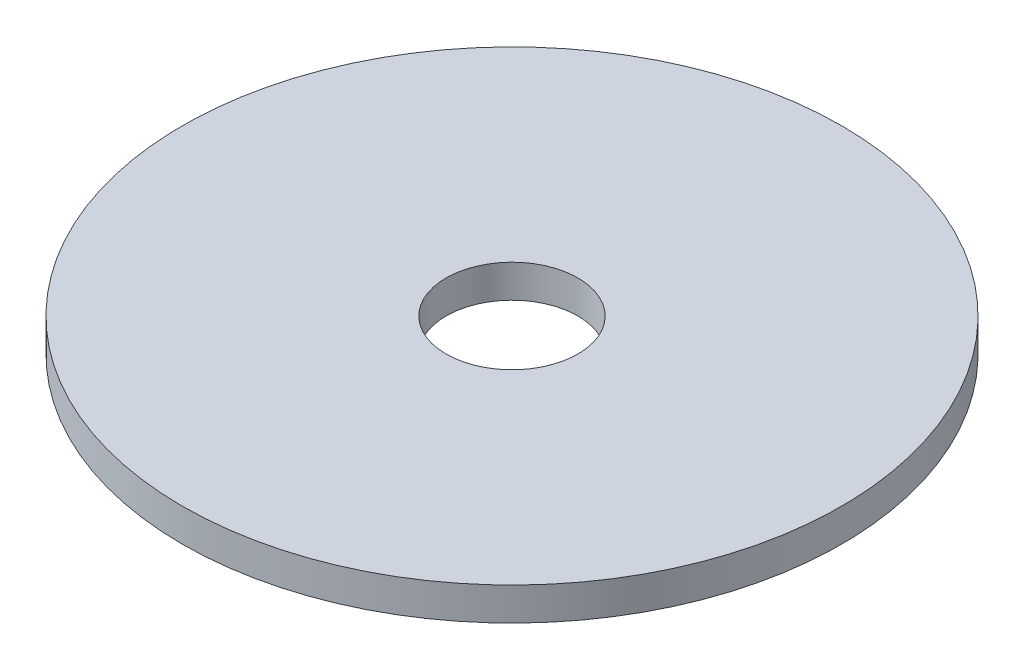
SolidWorks part; units mm, degrees
ref_plane "Front Plane" through (0, 0, 0) normal (0, 0, 1) x (1, 0, 0)
ref_plane "Top Plane" through (0, 0, 0) normal (0, 1, 0) x (1, 0, 0)
ref_plane "Right Plane" through (0, 0, 0) normal (1, 0, 0) x (0, 0, -1)
sketch "Sketch1" plane through (0, 0, 0) normal (0, 1, 0) x (1, 0, 0)
  circle A0 centre (0, 0) radius 50
  dimension "D1" = 100
extrude "Boss-Extrude1" add sketch "Sketch1" along normal blind 5
sketch "Sketch2" plane through (0, 5, 0) normal (0, 1, 0) x (1, 0, 0)
  circle A0 centre (0, 0) radius 10
extrude "Cut-Extrude1" cut sketch "Sketch2" against normal blind 5
